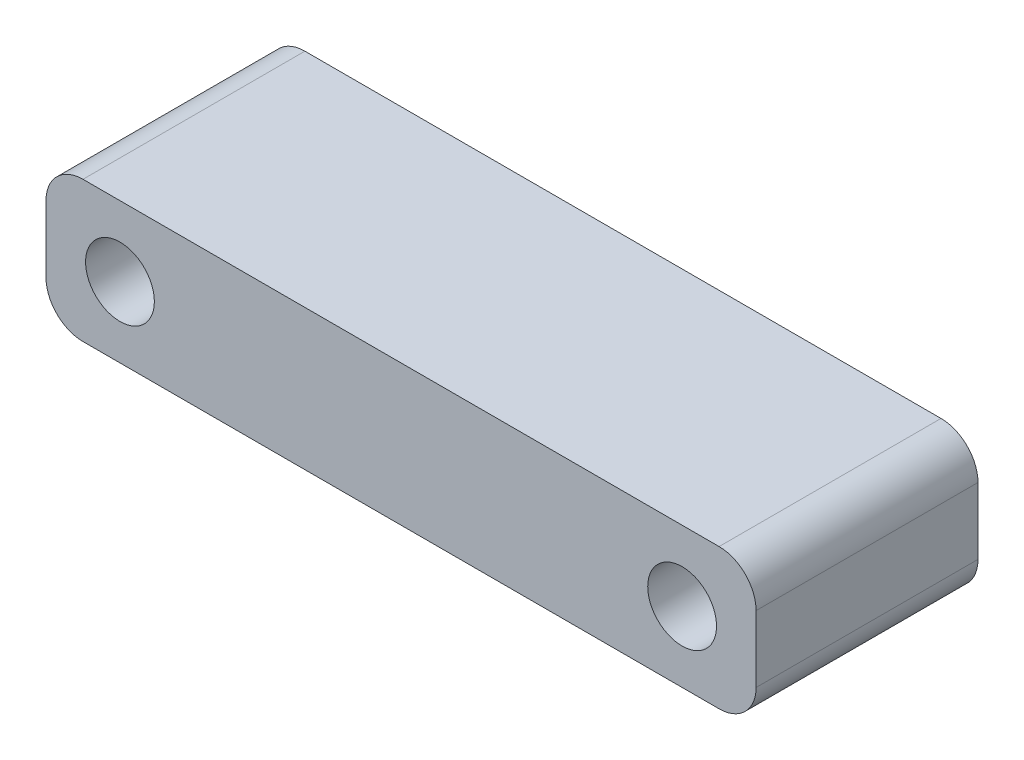
SolidWorks part; units mm, degrees
material "PLA"
ref_plane "前视基准面" through (0, 0, 0) normal (0, 0, 1) x (1, 0, 0)
ref_plane "上视基准面" through (0, 0, 0) normal (0, 1, 0) x (1, 0, 0)
ref_plane "右视基准面" through (0, 0, 0) normal (1, 0, 0) x (0, 0, -1)
other "Configuration Table"
sketch "草图1" plane through (0, 0, 0) normal (0, 0, 1) x (1, 0, 0)
  line L0 (0, 0) -> (0, 28.6568) construction
  line L1 (-48, 9.5) -> (48, 9.5)
  line L2 (-48, 9.5) -> (-48, -9.5)
  line L3 (-48, -9.5) -> (48, -9.5)
  line L4 (48, 9.5) -> (48, -9.5)
  line L5 (-48, 9.5) -> (48, -9.5) construction
  line L6 (-48, -9.5) -> (48, 9.5) construction
  circle A0 centre (-38, 0) radius 4.65
  circle A1 centre (38, 0) radius 4.65
  point P0 (0, 0)
  dimension "D3" = 76
  dimension "D4" = 9.3
  dimension "D1" = 96
  dimension "D2" = 19
extrude "凸台-拉伸1" add sketch "草图1" along normal blind 30
fillet "圆角1" radius 5 4 edges at (-48, -9.5, 15) (-48, 9.5, 15) (48, -9.5, 15) (48, 9.5, 15)
